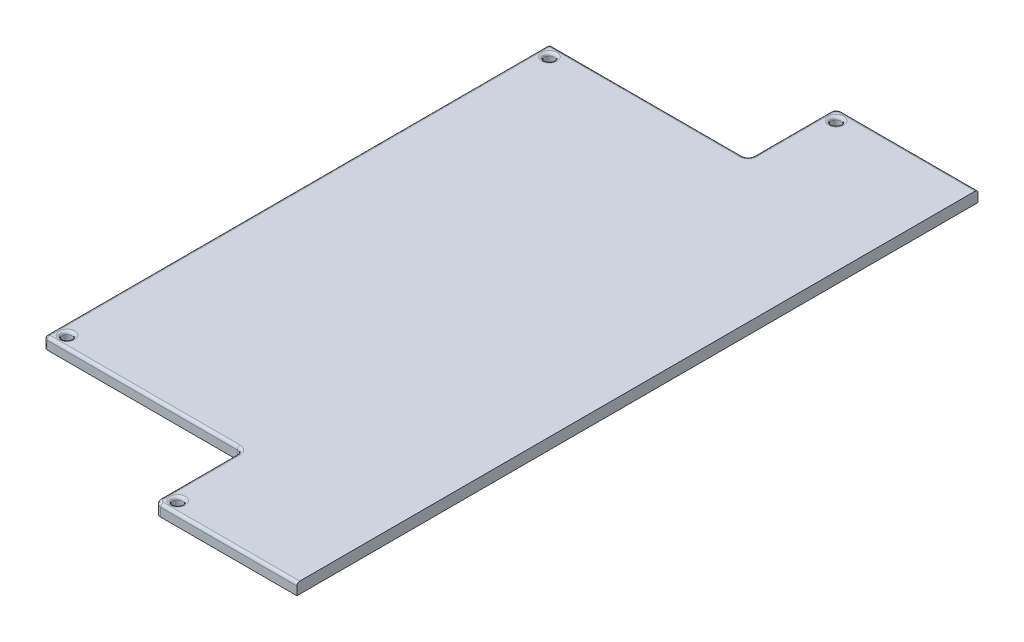
SolidWorks part; units mm, degrees
ref_plane "Front Plane" through (0, 0, 0) normal (0, 0, 1) x (1, 0, 0)
ref_plane "Top Plane" through (0, 0, 0) normal (0, 1, 0) x (1, 0, 0)
ref_plane "Right Plane" through (0, 0, 0) normal (1, 0, 0) x (0, 0, -1)
other "Configuration Table"
sketch "Sketch1" plane through (0, 0, 0) normal (0, 1, 0) x (1, 0, 0)
  line L0 (0, 0) -> (-120, 0) construction
  line L1 (0, 0) -> (0, 120)
  line L2 (0, 0) -> (0, -120)
  line L3 (-120, 0) -> (-120, 89)
  line L4 (-50, 120) -> (0, 120)
  line L5 (0, -120) -> (-50, -120)
  line L6 (-120, -89) -> (-120, 0)
  line L7 (-50, 120) -> (-50, 89)
  line L8 (-50, 89) -> (-120, 89)
  line L9 (-50, -120) -> (-50, -89)
  line L10 (-50, -89) -> (-120, -89)
  line L11 (-120, 89) -> (-120, 120) construction
  line L12 (-120, 120) -> (-50, 120) construction
  line L13 (-120, -120) -> (-120, -89) construction
  line L14 (-50, -120) -> (-120, -120) construction
  line L16 (-120, -81) -> (-112, -81) construction
  line L17 (-120, -81) -> (-120, -89) construction
  line L18 (-120, -89) -> (-112, -89) construction
  line L19 (-112, -81) -> (-112, -89) construction
  line L20 (-120, -81) -> (-112, -89) construction
  line L21 (-120, -89) -> (-112, -81) construction
  line L22 (-50, -112) -> (-42, -112) construction
  line L23 (-50, -112) -> (-50, -120) construction
  line L24 (-50, -120) -> (-42, -120) construction
  line L25 (-42, -112) -> (-42, -120) construction
  line L26 (-50, -112) -> (-42, -120) construction
  line L27 (-50, -120) -> (-42, -112) construction
  line L28 (-50, 120) -> (-42, 120) construction
  line L29 (-50, 120) -> (-50, 112) construction
  line L30 (-50, 112) -> (-42, 112) construction
  line L31 (-42, 120) -> (-42, 112) construction
  line L32 (-50, 120) -> (-42, 112) construction
  line L33 (-50, 112) -> (-42, 120) construction
  line L34 (-120, 89) -> (-112, 89) construction
  line L35 (-120, 89) -> (-120, 81) construction
  line L36 (-120, 81) -> (-112, 81) construction
  line L37 (-112, 89) -> (-112, 81) construction
  line L38 (-120, 89) -> (-112, 81) construction
  line L39 (-120, 81) -> (-112, 89) construction
  circle A0 centre (-46, -116) radius 1.7
  circle A1 centre (-116, -85) radius 1.7
  circle A2 centre (-116, 85) radius 1.7
  circle A3 centre (-46, 116) radius 1.7
  point P12 (-116, -85)
  point P18 (-46, -116)
  point P23 (-46, 116)
  point P28 (-116, 85)
  dimension "D5" = 3.4
  dimension "D1" = 240
  dimension "D2" = 70
  dimension "D3" = 31
  dimension "D4" = 8
extrude "Boss-Extrude1" add sketch "Sketch1" along normal blind 4
fillet "Fillet1" radius 2 4 edges at (-50, 2, -89) (-50, 2, -120) (-50, 2, 120) (-50, 2, 89)
fillet "Fillet2" radius 1 17 edges at (-24, 4, 120) (-49.4142, 4, 119.4142) (-50, 4, 104.5) (-50.5858, 4, 89.5858) (-24, 4, -120) (-49.4142, 4, -119.4142) (-50, 4, -104.5) (-50.5858, 4, -89.5858) (-46, 4, 117.7) (-116, 4, 86.7) (-116, 4, -83.3) (-46, 4, -114.3) (-86, 4, 89) (-86, 4, -89) (-120, 4, 0) (-120, 2, 89) (-120, 2, -89)
